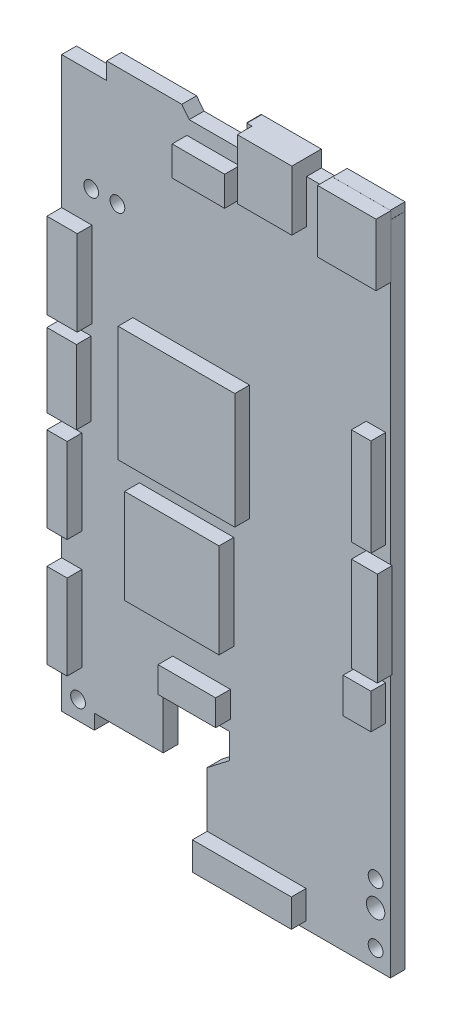
SolidWorks part; units mm, degrees
ref_plane "Plan de face" through (0, 0, 0) normal (0, 0, 1) x (1, 0, 0)
ref_plane "Plan de dessus" through (0, 0, 0) normal (0, 1, 0) x (1, 0, 0)
ref_plane "Plan de droite" through (0, 0, 0) normal (1, 0, 0) x (0, 0, -1)
sketch "Esquisse1" plane through (0, 0, 0) normal (0, 0, 1) x (1, 0, 0)
  line L1 (779.5964, 165.4855) -> (780.5988, 254.4798) construction
  line L2 (778.7964, 167.0147) -> (753.9964, 167.0147)
  line L3 (753.9964, 167.0147) -> (753.9964, 179.2847)
  line L4 (753.9964, 179.2847) -> (757.0464, 181.6309)
  line L5 (757.0464, 181.6309) -> (757.0464, 185.0309)
  line L6 (757.0464, 185.0309) -> (748.0464, 185.0309)
  line L7 (748.0464, 185.0309) -> (748.0464, 178.0309)
  line L8 (748.0464, 178.0309) -> (738.7348, 178.0309)
  line L9 (738.7348, 178.0309) -> (738.7348, 176.0309)
  line L10 (738.7348, 176.0309) -> (734.2964, 176.0309)
  line L11 (734.2964, 176.0309) -> (734.2964, 253.0309)
  line L12 (734.2964, 253.0309) -> (740.3927, 253.0309)
  line L13 (740.3927, 253.0309) -> (740.3927, 255.3309)
  line L14 (740.3927, 255.3309) -> (750.563, 255.3309)
  line L15 (750.563, 255.3309) -> (751.563, 254.0309)
  line L16 (751.563, 254.0309) -> (759.363, 254.0309)
  line L17 (759.363, 254.0309) -> (759.363, 257.5731)
  line L18 (759.363, 257.5731) -> (759.3809, 257.5731)
  line L19 (759.3809, 257.5731) -> (759.3809, 257.5309)
  line L20 (759.3809, 257.5309) -> (767.4547, 257.5309)
  line L21 (767.4547, 257.5309) -> (767.4547, 255.3066)
  line L22 (767.4547, 255.3066) -> (770.952, 255.3066)
  line L23 (770.952, 255.3066) -> (770.952, 257.0147)
  line L24 (770.952, 257.0147) -> (778.7842, 257.0147)
  line L25 (778.7842, 257.0147) -> (778.7842, 255.8947)
  line L26 (778.7842, 255.8947) -> (778.7964, 255.8947)
  line L27 (778.7964, 255.8947) -> (778.7964, 167.0147)
  dimension "D1" = 89
  dimension "D2" = 88.88
  dimension "D3" = 24.8
  dimension "D4" = 12.27
  dimension "D5" = 9
  dimension "D6" = 44.5
  dimension "D7" = 13.75
  dimension "D8" = 3.4
  dimension "D9" = 7
  dimension "D10" = 77
  dimension "D11" = 2.3
  dimension "D12" = 1
  dimension "D13" = 7.8
  dimension "D14" = 69
  dimension "D15" = 90
  dimension "D16" = 3.5
  dimension "D17" = 2
  dimension "D18" = 1.6401
extrude "Boss.-Extru.1" add sketch "Esquisse1" along normal blind 2
sketch "Esquisse3" plane through (0, 0, 2) normal (0, 0, -1) x (-1, 0, 0)
  line L1 (-759.7315, 227.0035) -> (-743.9382, 227.0035)
  line L2 (-759.7315, 227.0035) -> (-759.7315, 211.3356)
  line L3 (-759.7315, 211.3356) -> (-743.9382, 211.3356)
  line L4 (-743.9382, 227.0035) -> (-743.9382, 211.3356)
extrude "Boss.-Extru.3" add sketch "Esquisse3" against normal blind 2
sketch "Esquisse4" plane through (0, 0, 2) normal (0, 0, -1) x (-1, 0, 0)
  line L1 (-757.6006, 208.0767) -> (-744.8156, 208.0767)
  line L2 (-757.6006, 208.0767) -> (-757.6006, 195.2917)
  line L3 (-757.6006, 195.2917) -> (-744.8156, 195.2917)
  line L4 (-744.8156, 208.0767) -> (-744.8156, 195.2917)
extrude "Boss.-Extru.4" add sketch "Esquisse4" against normal blind 2
sketch "Esquisse5" plane through (0, 0, 2) normal (0, 0, -1) x (-1, 0, 0)
  line L1 (-778.8607, 257.0112) -> (-770.9412, 257.0112)
  line L2 (-778.8607, 257.0112) -> (-778.8607, 248.6132)
  line L3 (-778.8607, 248.6132) -> (-770.9412, 248.6132)
  line L4 (-770.9412, 257.0112) -> (-770.9412, 248.6132)
extrude "Boss.-Extru.5" add sketch "Esquisse5" against normal blind 2
sketch "Esquisse6" plane through (0, 0, 2) normal (0, 0, -1) x (-1, 0, 0)
  line L1 (-767.4547, 257.5309) -> (-760.076, 257.5309)
  line L2 (-767.4547, 257.5309) -> (-767.4547, 249.4255)
  line L3 (-767.4547, 249.4255) -> (-760.076, 249.4255)
  line L4 (-760.076, 257.5309) -> (-760.076, 249.4255)
extrude "Boss.-Extru.6" add sketch "Esquisse6" against normal blind 2
sketch "Esquisse7" plane through (0, 0, 2) normal (0, 0, -1) x (-1, 0, 0)
  line L0 (-753.9964, 179.2847) -> (-753.9964, 167.0147) construction
  line L1 (-778.1625, 230.6564) -> (-775.5296, 230.6564)
  line L2 (-778.1625, 230.6564) -> (-778.1625, 217.4918)
  line L3 (-778.1625, 217.4918) -> (-775.5296, 217.4918)
  line L4 (-775.5296, 230.6564) -> (-775.5296, 217.4918)
  line L5 (-779.0401, 215.4857) -> (-775.5296, 215.4857)
  line L6 (-779.0401, 215.4857) -> (-779.0401, 202.6972)
  line L7 (-779.0401, 202.6972) -> (-775.5296, 202.6972)
  line L8 (-775.5296, 215.4857) -> (-775.5296, 202.6972)
  line L9 (-774.4012, 196.5537) -> (-778.1625, 196.5537)
  line L10 (-774.4012, 196.5537) -> (-774.4012, 201.318)
  line L11 (-774.4012, 201.318) -> (-778.1625, 201.318)
  line L12 (-778.1625, 196.5537) -> (-778.1625, 201.318)
  line L13 (-757.1464, 186.5309) -> (-749.3464, 186.5309)
  line L14 (-757.1464, 186.5309) -> (-757.1464, 190.0309)
  line L15 (-757.1464, 190.0309) -> (-749.3464, 190.0309)
  line L16 (-749.3464, 186.5309) -> (-749.3464, 190.0309)
  line L17 (-753.9964, 171.8147) -> (-767.3964, 171.8147)
  line L18 (-753.9964, 171.8147) -> (-753.9964, 168.0147)
  line L19 (-753.9964, 168.0147) -> (-767.3964, 168.0147)
  line L20 (-767.3964, 171.8147) -> (-767.3964, 168.0147)
  line L21 (-734.2964, 253.0309) -> (-734.2964, 176.0309) construction
  line L22 (-737.0386, 182.5309) -> (-734.2964, 182.5309)
  line L23 (-737.0386, 182.5309) -> (-737.0386, 194.0309)
  line L24 (-737.0386, 194.0309) -> (-734.2964, 194.0309)
  line L25 (-734.2964, 182.5309) -> (-734.2964, 194.0309)
  line L26 (-734.2964, 176.0309) -> (-738.7348, 176.0309) construction
  line L27 (-737.0386, 198.5309) -> (-734.2964, 198.5309)
  line L28 (-737.0386, 198.5309) -> (-737.0386, 210.0309)
  line L29 (-737.0386, 210.0309) -> (-734.2964, 210.0309)
  line L30 (-734.2964, 198.5309) -> (-734.2964, 210.0309)
  line L31 (-738.2964, 212.0309) -> (-734.2964, 212.0309)
  line L32 (-738.2964, 212.0309) -> (-738.2964, 222.0309)
  line L33 (-738.2964, 222.0309) -> (-734.2964, 222.0309)
  line L34 (-734.2964, 212.0309) -> (-734.2964, 222.0309)
  line L35 (-758.363, 248.0309) -> (-751.253, 248.0309)
  line L36 (-758.363, 248.0309) -> (-758.363, 252.0309)
  line L37 (-758.363, 252.0309) -> (-751.253, 252.0309)
  line L38 (-751.253, 248.0309) -> (-751.253, 252.0309)
  line L40 (-734.2964, 223.5309) -> (-738.4064, 223.5309)
  line L41 (-734.2964, 223.5309) -> (-734.2964, 235.0809)
  line L42 (-734.2964, 235.0809) -> (-738.4064, 235.0809)
  line L43 (-738.4064, 223.5309) -> (-738.4064, 235.0809)
  line L44 (-734.2964, 223.5309) -> (-738.4064, 235.0809) construction
  line L45 (-734.2964, 235.0809) -> (-738.4064, 223.5309) construction
  line L47 (-748.0464, 185.0309) -> (-757.0464, 185.0309) construction
  line L49 (-748.0464, 178.0309) -> (-748.0464, 185.0309) construction
  line L50 (-753.9964, 167.0147) -> (-778.7964, 167.0147) construction
  line L51 (-759.363, 257.5731) -> (-759.363, 254.0309) construction
  line L52 (-759.363, 254.0309) -> (-751.563, 254.0309) construction
  point P42 (-736.3514, 229.3059)
  point P47 (0, 0)
  point P48 (0, 0)
  dimension "D1" = 6.5
  dimension "D2" = 2.7422
  dimension "D3" = 4.5
  dimension "D4" = 2.7422
  dimension "D5" = 11.5
  dimension "D6" = 11.5
  dimension "D7" = 2
  dimension "D8" = 10
  dimension "D9" = 4
  dimension "D10" = 1.5
  dimension "D11" = 11.55
  dimension "D12" = 4.11
  dimension "D13" = 3.5
  dimension "D14" = 7.8
  dimension "D15" = 1.5
  dimension "D16" = 1.3
  dimension "D17" = 3.8
  dimension "D18" = 13.4
  dimension "D19" = 1
  dimension "D20" = 1
  dimension "D21" = 7.11
  dimension "D22" = 4
  dimension "D23" = 2
extrude "Boss.-Extru.7" add sketch "Esquisse7" against normal blind 2
sketch "Esquisse8" [suppressed] plane through (0, 0, 0) normal (0, 0, -1) x (-1, 0, 0)
  line L1 (-748.9495, 251.8453) -> (-742.5552, 251.8453)
  line L2 (-748.9495, 251.8453) -> (-748.9495, 249.5885)
  line L3 (-748.9495, 249.5885) -> (-742.5552, 249.5885)
  line L4 (-742.5552, 251.8453) -> (-742.5552, 249.5885)
  line L5 (-771.7682, 246.3287) -> (-769.0099, 246.3287)
  line L6 (-771.7682, 246.3287) -> (-771.7682, 234.6685)
  line L7 (-771.7682, 234.6685) -> (-769.0099, 234.6685)
  line L8 (-769.0099, 246.3287) -> (-769.0099, 234.6685)
  line L9 (-778.1625, 193.7953) -> (-774.4012, 193.7953)
  line L10 (-778.1625, 193.7953) -> (-778.1625, 179.3769)
  line L11 (-778.1625, 179.3769) -> (-774.4012, 179.3769)
  line L12 (-774.4012, 193.7953) -> (-774.4012, 179.3769)
  line L13 (-737.6655, 219.7486) -> (-741.0507, 219.7486)
  line L14 (-737.6655, 219.7486) -> (-737.6655, 232.2863)
  line L15 (-737.6655, 232.2863) -> (-741.0507, 232.2863)
  line L16 (-741.0507, 219.7486) -> (-741.0507, 232.2863)
  line L17 (-739.3581, 175.2394) -> (-747.6957, 175.2394)
  line L18 (-739.3581, 175.2394) -> (-739.3581, 177.4962)
  line L19 (-739.3581, 177.4962) -> (-747.6957, 177.4962)
  line L20 (-747.6957, 175.2394) -> (-747.6957, 177.4962)
extrude "Boss.-Extru.8" [suppressed] add sketch "Esquisse8" along normal blind 2
sketch "Эскиз1" plane through (0, 0, 2) normal (0, 0, 1) x (1, 0, 0)
  line L0 (734.2964, 176.0309) -> (738.7348, 176.0309) construction
  line L1 (734.2964, 181.0309) -> (738.7348, 181.0309)
  line L2 (734.2964, 181.0309) -> (734.2964, 176.0309)
  line L3 (734.2964, 176.0309) -> (738.7348, 176.0309)
  line L4 (738.7348, 181.0309) -> (738.7348, 176.0309)
  line L5 (734.2964, 181.0309) -> (738.7348, 176.0309) construction
  line L6 (734.2964, 176.0309) -> (738.7348, 181.0309) construction
  circle A0 centre (736.5156, 178.5309) radius 1
  point P8 (0, 0)
  point P10 (0, 0)
  point P11 (735.1229, 176.0309)
  point P12 (0, 0)
  dimension "D1" = 2
  dimension "D2" = 2.5
sketch "Эскиз2" plane through (0, 0, 2) normal (0, 0, 1) x (1, 0, 0)
  line L1 (774.7964, 172.0147) -> (778.7964, 172.0147)
  line L2 (774.7964, 172.0147) -> (774.7964, 167.0147)
  line L3 (774.7964, 167.0147) -> (778.7964, 167.0147)
  line L4 (778.7964, 172.0147) -> (778.7964, 167.0147)
  line L5 (774.7964, 172.0147) -> (778.7964, 167.0147) construction
  line L6 (774.7964, 167.0147) -> (778.7964, 172.0147) construction
  circle A0 centre (776.7964, 169.5147) radius 1
  point P0 (776.7964, 169.5147)
  dimension "D3" = 2
  dimension "D1" = 4
  dimension "D2" = 5
sketch "Эскиз3" plane through (0, 0, 2) normal (0, 0, 1) x (1, 0, 0)
  line L0 (734.2964, 253.0309) -> (734.2964, 235.0809) construction
  line L1 (734.2964, 242.0809) -> (743.7964, 242.0809)
  line L2 (734.2964, 242.0809) -> (734.2964, 236.0809)
  line L3 (734.2964, 236.0809) -> (743.7964, 236.0809)
  line L4 (743.7964, 242.0809) -> (743.7964, 236.0809)
  line L5 (734.2964, 242.0809) -> (743.7964, 236.0809) construction
  line L6 (734.2964, 236.0809) -> (743.7964, 242.0809) construction
  line L7 (734.2964, 235.0809) -> (738.4064, 235.0809) construction
  line L8 (738.2964, 239.2809) -> (741.8464, 239.2809) construction
  line L9 (776.7964, 169.5147) -> (776.7964, 179.69) construction
  line L10 (774.7964, 167.0147) -> (778.7964, 172.0147) construction
  circle A0 centre (738.2964, 239.2809) radius 1
  circle A1 centre (741.8464, 239.2809) radius 1
  circle A2 centre (776.7964, 174.2147) radius 1.25
  circle A3 centre (776.7964, 177.6147) radius 1
  point P0 (739.0464, 239.0809)
  point P23 (0, 0)
  point P24 (0, 0)
  dimension "D4" = 2
  dimension "D5" = 2
  dimension "D10" = 3.4
  dimension "D11" = 2
  dimension "D12" = 2.5
  dimension "D1" = 1
  dimension "D2" = 9.5
  dimension "D3" = 6
  dimension "D6" = 3.55
  dimension "D7" = 4
  dimension "D8" = 2.8
  dimension "D9" = 4.7
extrude "Вырез-Вытянуть4" cut sketch "Эскиз3" against normal blind 10 contours A1 | A0 | A2 | A3
extrude "Вырез-Вытянуть5" cut sketch "Эскиз1" against normal blind 10 contours A0
extrude "Вырез-Вытянуть6" cut sketch "Эскиз2" against normal blind 10 contours A0
